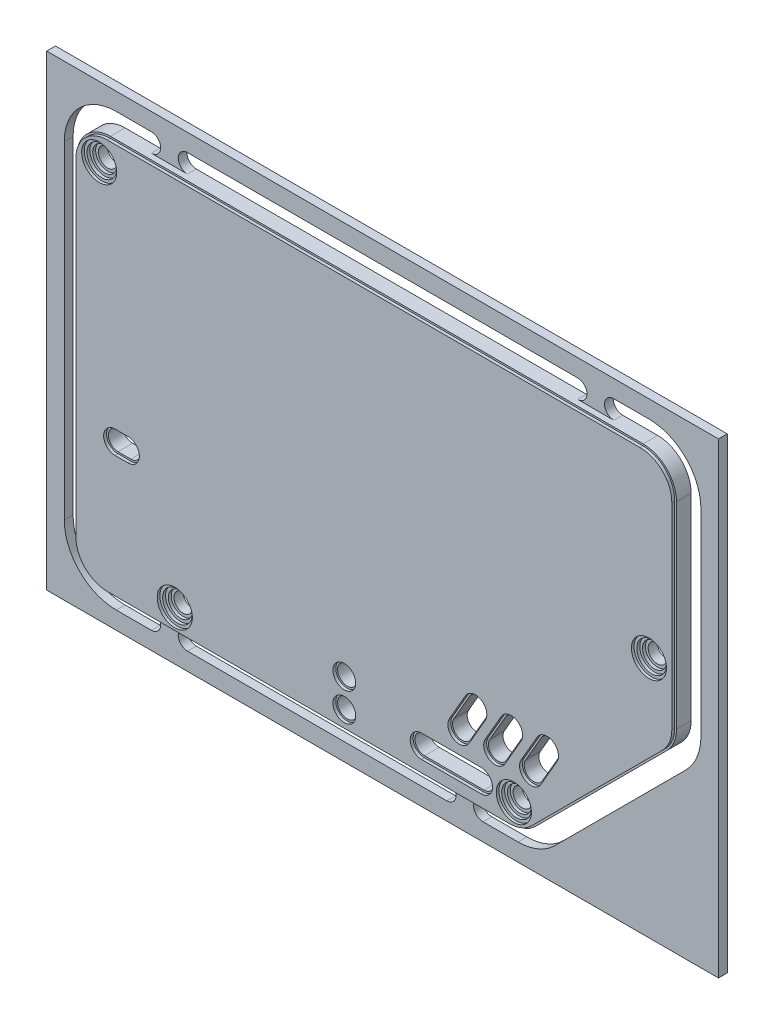
SolidWorks part; units mm, degrees
ref_plane "Front Plane" through (0, 0, 0) normal (0, 0, 1) x (1, 0, 0)
ref_plane "Top Plane" through (0, 0, 0) normal (0, 1, 0) x (1, 0, 0)
ref_plane "Right Plane" through (0, 0, 0) normal (1, 0, 0) x (0, 0, -1)
sketch "Sketch2" plane through (0, 0, 8.62) normal (0, 0, 1) x (1, 0, 0)
  line L0 (4.5, 66.2) -> (95.5, 66.2)
  line L1 (101.2, 60.5) -> (101.2, 26.864)
  line L2 (99.5305, 22.8335) -> (77.1665, 0.4695)
  line L3 (73.136, -1.2) -> (4.5, -1.2)
  line L4 (-1.2, 4.5) -> (-1.2, 60.5)
  line L5 (-1.5, 60.5) -> (-1.5, 4.5) construction
  arc A0 (4.5, -1.2) -> (-1.2, 4.5) centre (4.5, 4.5) cw
  arc A1 (77.1665, 0.4695) -> (73.136, -1.2) centre (73.136, 4.5) cw
  arc A2 (101.2, 26.864) -> (99.5305, 22.8335) centre (95.5, 26.864) cw
  arc A3 (95.5, 66.2) -> (101.2, 60.5) centre (95.5, 60.5) cw
  arc A4 (4.5, 66.2) -> (-1.2, 60.5) centre (4.5, 60.5) ccw
  arc A5 (-1.5, 4.5) -> (4.5, -1.5) centre (4.5, 4.5) ccw construction
  arc A6 (4.5, 66.5) -> (-1.5, 60.5) centre (4.5, 60.5) ccw construction
  arc A7 (101.5, 60.5) -> (95.5, 66.5) centre (95.5, 60.5) ccw construction
  arc A8 (73.136, -1.5) -> (77.3787, 0.2574) centre (73.136, 4.5) ccw construction
  circle A9 centre (3.0858, 61.9142) radius 1.5 construction
  circle A10 centre (16, 2.5) radius 1.5 construction
  circle A11 centre (73.9175, 2.659) radius 1.5 construction
  circle A12 centre (97, 35.5) radius 1.5 construction
  circle A13 centre (16, 2.5) radius 1.35 construction
  arc A14 (101.3205, 25.4074) -> (101.5, 26.864) centre (95.5, 26.864) ccw construction
  circle A15 centre (73.9175, 2.659) radius 1.35 construction
  circle A16 centre (97, 35.5) radius 1.35 construction
  circle A17 centre (3.0858, 61.9142) radius 1.35 construction
  dimension "D1" = 0.3
  dimension "D2" = 3
extrude "Boss-Extrude1" add sketch "Sketch2" along normal blind 3
hole_wizard "CSK for M3 Flat Head Machine Screw1" [suppressed] positions "Sketch4" profile "Sketch5" countersink size "M3" standard "ANSI Metric"
sketch "Sketch4" plane through (0, 0, 11.62) normal (0, 0, 1) x (1, 0, 0)
  point P0 (3.0858, 61.9142)
  point P3 (16, 2.5)
  point P6 (73.9175, 2.659)
  point P9 (97, 35.5)
sketch "Sketch5" plane through (3.0858, 61.9142, 11.62) normal (1, 0, 0) x (0, -1, 0)
  line L0 (0, 0) -> (0, 3)
  line L1 (0, 3) -> (1.7, 3)
  line L2 (1.7, 3) -> (1.7, 1.45)
  line L3 (1.7, 1.45) -> (3.15, 0)
  line L5 (3.15, 0) -> (0, 0)
  line L6 (-1.7, 1.45) -> (-3.15, 0) construction
  line L11 (0, -6.35) -> (0, 107.95) construction
  dimension "Thru Hole Dia." = 3.4
  dimension "Thru Hole Depth" = 3
  dimension "Near C'Sink Dia." = 6.3
  dimension "Near C'Sink Angle" = 90
sketch "Sketch6" plane through (0, 0, 11.62) normal (0, 0, 1) x (1, 0, 0)
  line L6 (72.0938, 16.422) -> (72.0938, 14.1605) construction
  line L8 (78.5938, 16.422) -> (65.5938, 16.422) construction
  line L10 (68.326, 3.048) -> (58.166, 3.048) construction
  line L11 (68.326, 1.398) -> (58.166, 1.398)
  line L12 (68.326, 4.698) -> (58.166, 4.698)
  line L13 (72.0938, 7.6835) -> (72.0938, 5.422) construction
  line L14 (65.5938, 5.422) -> (78.5938, 5.422) construction
  arc A4 (68.326, 1.398) -> (68.326, 4.698) centre (68.326, 3.048) ccw
  arc A5 (58.166, 4.698) -> (58.166, 1.398) centre (58.166, 3.048) ccw
  point P26 (63.246, 3.048)
  dimension "D4" = 3.3
extrude "Cut-Extrude1" cut sketch "Sketch6" against normal through all
sketch "Sketch7" plane through (0, 0, 11.62) normal (0, 0, 1) x (1, 0, 0)
  line L1 (19.25, 57.135) -> (67.25, 57.135)
  line L2 (18.615, 56.5) -> (18.615, 20.1)
  line L3 (19.25, 19.465) -> (67.25, 19.465)
  line L4 (67.885, 56.5) -> (67.885, 20.1)
  arc A4 (67.25, 57.135) -> (67.885, 56.5) centre (67.25, 56.5) cw
  arc A5 (67.25, 19.465) -> (67.885, 20.1) centre (67.25, 20.1) ccw
  arc A6 (18.615, 20.1) -> (19.25, 19.465) centre (19.25, 20.1) ccw
  arc A7 (19.25, 57.135) -> (18.615, 56.5) centre (19.25, 56.5) ccw
  dimension "D2" = 0.635
split line "Split Line1" [suppressed]
sketch "Sketch8" plane through (0, 0, 11.62) normal (0, 0, 1) x (1, 0, 0)
  circle A0 centre (44.958, 2.54) radius 1
  circle A1 centre (44.958, 6.096) radius 1
  dimension "D1" = 2
extrude "Cut-Extrude2" cut sketch "Sketch8" against normal blind 10
sketch "Sketch9" plane through (0, 0, 11.62) normal (0, 0, 1) x (1, 0, 0)
  line L0 (65.0938, 10.922) -> (68.5938, 10.922) construction
  line L1 (68.5938, 10.922) -> (72.0938, 10.922) construction
  line L2 (72.0938, 10.922) -> (75.5938, 10.922) construction
  line L3 (75.5938, 10.922) -> (79.0938, 10.922) construction
  line L4 (66.8438, 13.9531) -> (66.8438, 7.8909) construction
  line L5 (65.0938, 10.922) -> (66.8438, 7.8909) construction
  line L6 (70.3438, 7.8909) -> (70.3438, 13.9531) construction
  line L7 (72.0938, 15.272) -> (72.0938, 6.572) construction
  line L8 (73.8438, 13.9531) -> (73.8438, 7.8909) construction
  line L9 (75.8938, 15.272) -> (68.2938, 15.272) construction
  line L10 (77.3438, 7.8909) -> (77.3438, 13.9531) construction
  line L11 (68.2938, 6.572) -> (75.8938, 6.572) construction
  circle A0 centre (65.0938, 10.922) radius 1
  circle A1 centre (68.5938, 10.922) radius 1
  circle A2 centre (72.0938, 10.922) radius 1
  circle A3 centre (75.5938, 10.922) radius 1
  circle A4 centre (79.0938, 10.922) radius 1
  circle A5 centre (66.8438, 13.9531) radius 1
  circle A6 centre (70.3438, 13.9531) radius 1
  circle A7 centre (73.8438, 13.9531) radius 1
  circle A8 centre (77.3438, 13.9531) radius 1
  circle A9 centre (66.8438, 7.8909) radius 1
  circle A10 centre (70.3438, 7.8909) radius 1
  circle A11 centre (73.8438, 7.8909) radius 1
  circle A12 centre (77.3438, 7.8909) radius 1
  circle A13 centre (44.958, 6.096) radius 1 construction
  point P18 (66.8438, 10.922)
  point P19 (70.3438, 10.922)
  point P20 (73.8438, 10.922)
  point P21 (77.3438, 10.922)
  dimension "D1" = 3.5
extrude "Cut-Extrude3" [suppressed] cut sketch "Sketch9" against normal blind 10
sketch "Sketch10" plane through (0, 0, 11.62) normal (0, 0, 1) x (1, 0, 0)
  line L0 (5.1479, 21.844) -> (8.6479, 21.844) construction
  line L1 (6.8979, 23.4191) -> (6.8979, 20.2689) construction
  circle A0 centre (5.1479, 21.844) radius 1
  circle A1 centre (8.6479, 21.844) radius 1
  circle A2 centre (44.958, 6.096) radius 1 construction
  point P12 (6.8979, 21.844)
  dimension "D1" = 3.5
extrude "Cut-Extrude4" cut sketch "Sketch10" against normal blind 10
chamfer "Chamfer1" [suppressed] distance 0.5 angle 45
sketch "Sketch12" plane through (0, 0, 11.62) normal (0, 0, 1) x (1, 0, 0)
  line L0 (5.7979, 21.844) -> (7.9979, 21.844) construction
  line L1 (5.7979, 23.494) -> (7.9979, 23.494)
  line L2 (5.7979, 20.194) -> (7.9979, 20.194)
  line L3 (44.958, 6.746) -> (44.958, 1.89) construction
  line L4 (42.6658, 5.096) -> (46.9218, 5.096) construction
  line L5 (46.9218, 3.54) -> (42.9064, 3.54) construction
  line L6 (70.7191, 8.5409) -> (73.4686, 13.3031) construction
  line L7 (69.2902, 9.3659) -> (72.0396, 14.1281)
  line L8 (72.1481, 7.7159) -> (74.8975, 12.4781)
  line L9 (66.658, 6.8909) -> (75.9903, 6.8909) construction
  line L10 (71.007, 14.9531) -> (76.3222, 14.9531) construction
  line L11 (64.5992, 8.5409) -> (67.3486, 13.3031) construction
  line L12 (63.1703, 9.3659) -> (65.9197, 14.1281)
  line L13 (66.0281, 7.7159) -> (68.7776, 12.4781)
  line L14 (76.839, 8.5409) -> (79.5885, 13.3031) construction
  line L15 (75.4101, 9.3659) -> (78.1595, 14.1281)
  line L16 (78.268, 7.7159) -> (81.0174, 12.4781)
  arc A0 (5.7979, 23.494) -> (5.7979, 20.194) centre (5.7979, 21.844) ccw
  arc A1 (7.9979, 20.194) -> (7.9979, 23.494) centre (7.9979, 21.844) ccw
  circle A2 centre (5.1479, 21.844) radius 1 construction
  circle A3 centre (8.6479, 21.844) radius 1 construction
  circle A4 centre (44.958, 6.746) radius 1.65
  circle A5 centre (44.958, 1.89) radius 1.65
  circle A6 centre (73.8438, 13.9531) radius 1 construction
  circle A7 centre (44.958, 6.096) radius 1 construction
  circle A8 centre (44.958, 2.54) radius 1 construction
  arc A9 (69.2902, 9.3659) -> (72.1481, 7.7159) centre (70.7191, 8.5409) ccw
  arc A10 (74.8975, 12.4781) -> (72.0396, 14.1281) centre (73.4686, 13.3031) ccw
  arc A11 (63.1703, 9.3659) -> (66.0281, 7.7159) centre (64.5992, 8.5409) ccw
  circle A12 centre (70.3438, 7.8909) radius 1 construction
  arc A13 (68.7776, 12.4781) -> (65.9197, 14.1281) centre (67.3486, 13.3031) ccw
  arc A14 (75.4101, 9.3659) -> (78.268, 7.7159) centre (76.839, 8.5409) ccw
  arc A15 (81.0174, 12.4781) -> (78.1595, 14.1281) centre (79.5885, 13.3031) ccw
  point P2 (6.8979, 21.844)
  point P7 (4.1479, 21.844)
  point P8 (4.1479, 21.844)
  point P11 (9.6479, 21.844)
  point P12 (9.6479, 21.844)
  point P13 (5.1479, 21.844)
  point P21 (44.958, 6.096)
  point P33 (72.0938, 10.922)
  point P50 (65.9739, 10.922)
  point P55 (78.2137, 10.922)
  dimension "D2" = 3.3
  dimension "D1" = 3.3
  dimension "D3" = 3.3
  dimension "D4" = 2
  dimension "D5" = 2
extrude "Cut-Extrude5" cut sketch "Sketch12" against normal blind 10
chamfer "Chamfer2" [suppressed] distance 0.5 angle 45
sketch "Sketch13" plane through (0, 0, 11.62) normal (0, 0, 1) x (1, 0, 0)
  line L83 (95.5, 65.9) -> (4.5, 65.9)
  line L84 (-0.9, 60.5) -> (-0.9, 4.5)
  line L85 (4.5, -0.9) -> (73.136, -0.9)
  line L86 (76.9544, 0.6816) -> (99.3184, 23.0456)
  line L87 (100.9, 26.864) -> (100.9, 60.5)
  line L88 (95.5, 65.9) -> (4.5, 65.9)
  line L89 (-0.9, 60.5) -> (-0.9, 4.5)
  line L90 (4.5, -0.9) -> (73.136, -0.9)
  line L91 (76.9544, 0.6816) -> (99.3184, 23.0456)
  line L92 (100.9, 26.864) -> (100.9, 60.5)
  line L424 (5.7979, 19.894) -> (7.9979, 19.894)
  line L425 (7.9979, 23.794) -> (5.7979, 23.794)
  line L426 (5.7979, 19.894) -> (7.9979, 19.894)
  line L427 (7.9979, 23.794) -> (5.7979, 23.794)
  line L434 (58.166, 1.098) -> (68.326, 1.098)
  line L435 (68.326, 4.998) -> (58.166, 4.998)
  line L436 (58.166, 1.098) -> (68.326, 1.098)
  line L437 (68.326, 4.998) -> (58.166, 4.998)
  line L444 (66.288, 7.5659) -> (69.0374, 12.3281)
  line L445 (65.6599, 14.2781) -> (62.9105, 9.5159)
  line L446 (66.288, 7.5659) -> (69.0374, 12.3281)
  line L447 (65.6599, 14.2781) -> (62.9105, 9.5159)
  line L454 (72.4079, 7.5659) -> (75.1573, 12.3281)
  line L455 (71.7798, 14.2781) -> (69.0304, 9.5159)
  line L456 (72.4079, 7.5659) -> (75.1573, 12.3281)
  line L457 (71.7798, 14.2781) -> (69.0304, 9.5159)
  line L464 (78.5278, 7.5659) -> (81.2772, 12.3281)
  line L465 (77.8997, 14.2781) -> (75.1503, 9.5159)
  line L466 (78.5278, 7.5659) -> (81.2772, 12.3281)
  line L467 (77.8997, 14.2781) -> (75.1503, 9.5159)
  arc A86 (4.5, 65.9) -> (-0.9, 60.5) centre (4.5, 60.5) ccw
  arc A87 (-0.9, 4.5) -> (4.5, -0.9) centre (4.5, 4.5) ccw
  arc A88 (73.136, -0.9) -> (76.9544, 0.6816) centre (73.136, 4.5) ccw
  arc A89 (99.3184, 23.0456) -> (100.9, 26.864) centre (95.5, 26.864) ccw
  arc A90 (100.9, 60.5) -> (95.5, 65.9) centre (95.5, 60.5) ccw
  arc A91 (4.5, 65.9) -> (-0.9, 60.5) centre (4.5, 60.5) ccw
  arc A92 (-0.9, 4.5) -> (4.5, -0.9) centre (4.5, 4.5) ccw
  arc A93 (73.136, -0.9) -> (76.9544, 0.6816) centre (73.136, 4.5) ccw
  arc A94 (99.3184, 23.0456) -> (100.9, 26.864) centre (95.5, 26.864) ccw
  arc A95 (100.9, 60.5) -> (95.5, 65.9) centre (95.5, 60.5) ccw
  arc A506 (5.7979, 23.794) -> (5.7979, 19.894) centre (5.7979, 21.844) ccw
  arc A507 (7.9979, 19.894) -> (7.9979, 23.794) centre (7.9979, 21.844) ccw
  arc A508 (5.7979, 23.794) -> (5.7979, 19.894) centre (5.7979, 21.844) ccw
  arc A509 (7.9979, 19.894) -> (7.9979, 23.794) centre (7.9979, 21.844) ccw
  circle A510 centre (44.958, 6.746) radius 1.95
  circle A511 centre (44.958, 6.746) radius 1.95
  circle A513 centre (44.958, 1.89) radius 1.95
  circle A514 centre (44.958, 1.89) radius 1.95
  arc A520 (68.326, 1.098) -> (68.326, 4.998) centre (68.326, 3.048) ccw
  arc A521 (58.166, 4.998) -> (58.166, 1.098) centre (58.166, 3.048) ccw
  arc A522 (68.326, 1.098) -> (68.326, 4.998) centre (68.326, 3.048) ccw
  arc A523 (58.166, 4.998) -> (58.166, 1.098) centre (58.166, 3.048) ccw
  arc A528 (69.0374, 12.3281) -> (65.6599, 14.2781) centre (67.3486, 13.3031) ccw
  arc A529 (62.9105, 9.5159) -> (66.288, 7.5659) centre (64.5992, 8.5409) ccw
  arc A530 (69.0374, 12.3281) -> (65.6599, 14.2781) centre (67.3486, 13.3031) ccw
  arc A531 (62.9105, 9.5159) -> (66.288, 7.5659) centre (64.5992, 8.5409) ccw
  arc A536 (69.0304, 9.5159) -> (72.4079, 7.5659) centre (70.7191, 8.5409) ccw
  arc A537 (75.1573, 12.3281) -> (71.7798, 14.2781) centre (73.4686, 13.3031) ccw
  arc A538 (69.0304, 9.5159) -> (72.4079, 7.5659) centre (70.7191, 8.5409) ccw
  arc A539 (75.1573, 12.3281) -> (71.7798, 14.2781) centre (73.4686, 13.3031) ccw
  arc A544 (75.1503, 9.5159) -> (78.5278, 7.5659) centre (76.839, 8.5409) ccw
  arc A545 (81.2772, 12.3281) -> (77.8997, 14.2781) centre (79.5885, 13.3031) ccw
  arc A546 (75.1503, 9.5159) -> (78.5278, 7.5659) centre (76.839, 8.5409) ccw
  arc A547 (81.2772, 12.3281) -> (77.8997, 14.2781) centre (79.5885, 13.3031) ccw
  line M33 (81.0174, 12.4781) -> (78.268, 7.7159)
  arc M34 (78.268, 7.7159) -> (75.4101, 9.3659) centre (76.839, 8.5409) cw
  line M35 (75.4101, 9.3659) -> (78.1595, 14.1281)
  arc M36 (78.1595, 14.1281) -> (81.0174, 12.4781) centre (79.5885, 13.3031) cw
  line M37 (68.7776, 12.4781) -> (66.0281, 7.7159)
  arc M38 (66.0281, 7.7159) -> (63.1703, 9.3659) centre (64.5992, 8.5409) cw
  line M39 (63.1703, 9.3659) -> (65.9197, 14.1281)
  arc M40 (65.9197, 14.1281) -> (68.7776, 12.4781) centre (67.3486, 13.3031) cw
  line M41 (74.8975, 12.4781) -> (72.1481, 7.7159)
  arc M42 (72.1481, 7.7159) -> (69.2902, 9.3659) centre (70.7191, 8.5409) cw
  line M43 (69.2902, 9.3659) -> (72.0396, 14.1281)
  arc M44 (72.0396, 14.1281) -> (74.8975, 12.4781) centre (73.4686, 13.3031) cw
  circle M45 centre (44.958, 1.89) radius 1.65
  circle M46 centre (44.958, 6.746) radius 1.65
  line M47 (7.9979, 20.194) -> (5.7979, 20.194)
  arc M48 (5.7979, 20.194) -> (5.7979, 23.494) centre (5.7979, 21.844) cw
  line M49 (5.7979, 23.494) -> (7.9979, 23.494)
  arc M50 (7.9979, 23.494) -> (7.9979, 20.194) centre (7.9979, 21.844) cw
  line M51 (58.166, 4.698) -> (68.326, 4.698)
  arc M52 (68.326, 4.698) -> (68.326, 1.398) centre (68.326, 3.048) cw
  line M53 (68.326, 1.398) -> (58.166, 1.398)
  arc M54 (58.166, 1.398) -> (58.166, 4.698) centre (58.166, 3.048) cw
  arc M56 (-1.2, 4.5) -> (4.5, -1.2) centre (4.5, 4.5) ccw
  line M57 (4.5, -1.2) -> (73.136, -1.2)
  arc M58 (73.136, -1.2) -> (77.1665, 0.4695) centre (73.136, 4.5) ccw
  line M59 (77.1665, 0.4695) -> (99.5305, 22.8335)
  arc M60 (99.5305, 22.8335) -> (101.2, 26.864) centre (95.5, 26.864) ccw
  line M61 (101.2, 26.864) -> (101.2, 60.5)
  arc M62 (101.2, 60.5) -> (95.5, 66.2) centre (95.5, 60.5) ccw
  line M63 (95.5, 66.2) -> (4.5, 66.2)
  arc M64 (4.5, 66.2) -> (-1.2, 60.5) centre (4.5, 60.5) ccw
  line M65 (-1.2, 60.5) -> (-1.2, 4.5)
  dimension "D1" = 0.3
  dimension "D2" = 0.3
  dimension "D3" = 0.3
  dimension "D4" = 0.3
  dimension "D5" = 0.3
  dimension "D6" = 0.3
  dimension "D7" = 0.3
  dimension "D8" = 0.3
extrude "Cut-Extrude6" cut sketch "Sketch13" against normal blind 0.5 contours A95 L92 A94 L91 A93 L90 A92 L89 A91 L88 M65 M56 M57 M58 M59 M60 M61 M62 M63 M64 | L426 A509 L427 A508 M50 M47 M48 M49 | A511 M46 | A514 M45 | L437 A523 L436 A522 M54 M51 M52 M53 | L447 A531 L446 A530 M40 M37 M38 M39 | L456 A539 L457 A538 M44 M41 M42 M43 | L466 A547 L467 A546 M36 M33 M34 M35
ref_plane "Plane1" through (0, 2.5, 0) normal (0, -1, 0) x (-1, 0, 0)
sketch "Sketch14" plane through (0, 2.5, 0) normal (0, -1, 0) x (-1, 0, 0)
  line L0 (-16, -11.62) -> (-16, -8.62)
  line L1 (-4.5, -8.62) -> (-73.136, -8.62) construction
  line L2 (-16, -8.62) -> (-17.5875, -8.62)
  line L3 (-17.5875, -8.62) -> (-17.5875, -9.92)
  line L4 (-17.5875, -9.92) -> (-19, -11.42) construction
  line L5 (-19, -11.42) -> (-19, -11.62)
  line L6 (-4.5, -11.62) -> (-73.136, -11.62) construction
  line L7 (-19, -11.62) -> (-16, -11.62)
  line L8 (-17.5875, -9.92) -> (-17.5875, -10.17)
  line L9 (-17.5875, -10.17) -> (-18.0583, -10.17)
  line L10 (-18.0583, -10.17) -> (-18.0583, -10.67)
  line L11 (-18.0583, -10.67) -> (-18.5292, -10.67)
  line L12 (-18.5292, -10.67) -> (-18.5292, -11.17)
  line L13 (-18.5292, -11.17) -> (-19, -11.17)
  line L14 (-19, -11.17) -> (-19, -11.42)
  point P16 (-17.8229, -10.17)
  point P18 (-18.0583, -10.42)
  point P19 (-18.2938, -10.67)
  point P20 (-18.5292, -10.92)
  point P21 (-18.7646, -11.17)
  dimension "D1" = 3
  dimension "D2" = 1.5875
  dimension "D3" = 0.2
  dimension "D4" = 1.5
revolve "Cut-Revolve1" cut sketch "Sketch14" angle 360 about L0
pattern_sketch "Sketch-Pattern1" of "Cut-Revolve1" driven by "Sketch4"
sketch "Sketch15" plane through (0, 0, 8.62) normal (0, 0, -1) x (-1, 0, 0)
  line L0 (-95.5, 66.2) -> (-4.5, 66.2) construction
  line L1 (-4.5, -1.2) -> (-73.136, -1.2) construction
  line L33 (-84.9125, 67.7875) -> (-87.9125, 67.7875) construction
  line L34 (-12.0875, 67.7875) -> (-15.0875, 67.7875) construction
  line L35 (-12.0875, -2.7875) -> (-15.0875, -2.7875) construction
  line L36 (-62.5485, -2.7875) -> (-65.5485, -2.7875) construction
  line L38 (4.375, 4.5) -> (4.375, 60.5)
  line L39 (-4.5, 69.375) -> (-95.5, 69.375)
  line L40 (-104.375, 60.5) -> (-104.375, 26.864)
  line L41 (-101.7756, 20.5884) -> (-79.4116, -1.7756)
  line L42 (-73.136, -4.375) -> (-4.5, -4.375)
  line L43 (4.375, 4.5) -> (4.375, 60.5)
  line L44 (-4.5, 69.375) -> (-95.5, 69.375)
  line L45 (-104.375, 60.5) -> (-104.375, 26.864)
  line L46 (-101.7756, 20.5884) -> (-79.4116, -1.7756)
  line L47 (-73.136, -4.375) -> (-4.5, -4.375)
  line L48 (7.375, 72.375) -> (-107.375, 72.375)
  line L49 (7.375, 72.375) -> (7.375, -7.375)
  line L50 (7.375, -7.375) -> (-107.375, -7.375)
  line L51 (-107.375, 72.375) -> (-107.375, -7.375)
  arc A0 (-10.5, 66.2) -> (-10.5, 69.375) centre (-10.5, 67.7875) cw
  arc A1 (-16.675, 66.2) -> (-16.675, 69.375) centre (-16.675, 67.7875) ccw
  arc A2 (-83.325, 66.2) -> (-83.325, 69.375) centre (-83.325, 67.7875) cw
  arc A3 (-89.5, 66.2) -> (-89.5, 69.375) centre (-89.5, 67.7875) ccw
  arc A4 (-10.5, -1.2) -> (-10.5, -4.375) centre (-10.5, -2.7875) ccw
  arc A5 (-16.675, -1.2) -> (-16.675, -4.375) centre (-16.675, -2.7875) cw
  arc A6 (-60.961, -1.2) -> (-60.961, -4.375) centre (-60.961, -2.7875) ccw
  arc A7 (-67.136, -1.2) -> (-67.136, -4.375) centre (-67.136, -2.7875) cw
  arc A39 (-4.5, -4.375) -> (4.375, 4.5) centre (-4.5, 4.5) ccw
  arc A40 (4.375, 60.5) -> (-4.5, 69.375) centre (-4.5, 60.5) ccw
  arc A41 (-95.5, 69.375) -> (-104.375, 60.5) centre (-95.5, 60.5) ccw
  arc A42 (-104.375, 26.864) -> (-101.7756, 20.5884) centre (-95.5, 26.864) ccw
  arc A43 (-79.4116, -1.7756) -> (-73.136, -4.375) centre (-73.136, 4.5) ccw
  arc A44 (-4.5, -4.375) -> (4.375, 4.5) centre (-4.5, 4.5) ccw
  arc A45 (4.375, 60.5) -> (-4.5, 69.375) centre (-4.5, 60.5) ccw
  arc A46 (-95.5, 69.375) -> (-104.375, 60.5) centre (-95.5, 60.5) ccw
  arc A47 (-104.375, 26.864) -> (-101.7756, 20.5884) centre (-95.5, 26.864) ccw
  arc A48 (-79.4116, -1.7756) -> (-73.136, -4.375) centre (-73.136, 4.5) ccw
  line M38 (-4.5, 66.2) -> (-95.5, 66.2)
  line M44 (-73.136, -1.2) -> (-4.5, -1.2)
  dimension "D2" = 3
  dimension "D3" = 6
  dimension "D4" = 6
  dimension "D5" = 6
  dimension "D6" = 3
  dimension "D7" = 3
  dimension "D8" = 3
  dimension "D9" = 3
  dimension "D1" = 3.175
extrude "Boss-Extrude2" add sketch "Sketch15" against normal blind 1.5 contours A5 L47 A4 M44 | L48 L51 L50 L49 A48 L46 A47 L45 A46 L44 A45 L43 A44 L47 | A7 L47 A6 M44 | A1 A0 L44 M38 | A3 A2 L44 M38
